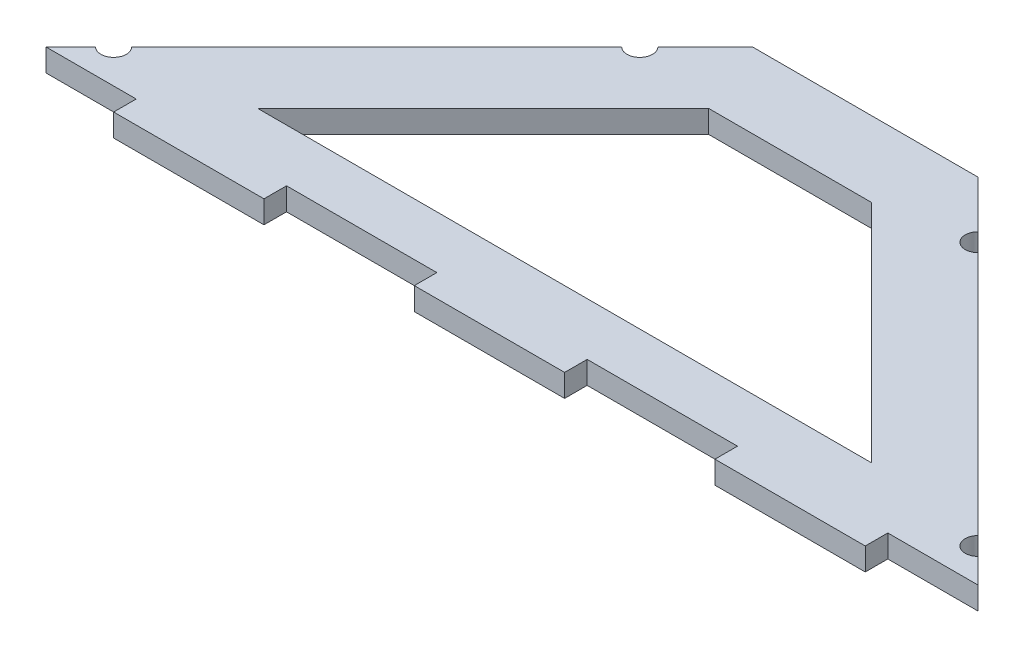
SolidWorks part; units mm, degrees
ref_plane "Front Plane" through (0, 0, 0) normal (0, 0, 1) x (1, 0, 0)
ref_plane "Top Plane" through (0, 0, 0) normal (0, 1, 0) x (1, 0, 0)
ref_plane "Right Plane" through (0, 0, 0) normal (1, 0, 0) x (0, 0, -1)
sketch "Sketch1" plane through (0, 0, 0) normal (0, 1, 0) x (1, 0, 0)
  line L0 (-55, 55) -> (-55, -55)
  line L1 (-65, 65) -> (65, 65)
  line L2 (-65, 65) -> (-65, -65)
  line L3 (-65, -65) -> (65, -65)
  line L4 (65, 65) -> (65, -65)
  line L5 (-65, 65) -> (65, -65) construction
  line L6 (-65, -65) -> (65, 65) construction
  line L7 (-55, -55) -> (55, -55)
  line L8 (55, 55) -> (55, -55)
  line L9 (-55, 55) -> (55, 55)
  line L10 (-15, 15) -> (-15, -15)
  line L11 (-15, -15) -> (15, -15)
  line L12 (15, 15) -> (15, -15)
  line L13 (-15, 15) -> (15, 15)
  line L14 (-25, 25) -> (-25, -25)
  line L15 (-25, -25) -> (25, -25)
  line L16 (25, 25) -> (25, -25)
  line L17 (-25, 25) -> (25, 25)
  line L18 (-55, -55) -> (-25, -25)
  line L19 (-47.9289, -62.0711) -> (-10.8579, -25)
  line L20 (-62.0711, -47.9289) -> (-25, -10.8579)
  line L21 (-62.0711, -47.9289) -> (-32.0711, -17.9289) construction
  line L22 (-47.9289, -62.0711) -> (-17.9289, -32.0711) construction
  line L23 (-47.9289, 62.0711) -> (-10.8579, 25)
  line L24 (-62.0711, 47.9289) -> (-25, 10.8579)
  line L25 (62.0711, 47.9289) -> (25, 10.8579)
  line L26 (47.9289, 62.0711) -> (10.8579, 25)
  line L27 (47.9289, -62.0711) -> (10.8579, -25)
  line L28 (62.0711, -47.9289) -> (25, -10.8579)
  point P0 (0, 0)
  point P39 (0, 0)
  dimension "D1" = 130
  dimension "D2" = 10
  dimension "D3" = 40
  dimension "D4" = 10
  dimension "D5" = 10
  dimension "D6" = 10
  dimension "D7" = 4
extrude "Boss-Extrude1" add sketch "Sketch1" along normal blind 3
sketch "Sketch2" plane through (0, 3, 0) normal (0, 1, 0) x (1, 0, 0)
  line L1 (-57.5, -57.5) -> (57.5, -57.5)
  line L2 (-57.5, -57.5) -> (-57.5, 57.5)
  line L3 (-57.5, 57.5) -> (57.5, 57.5)
  line L4 (57.5, -57.5) -> (57.5, 57.5)
  line L5 (-57.5, -57.5) -> (57.5, 57.5) construction
  line L6 (-57.5, 57.5) -> (57.5, -57.5) construction
  circle A0 centre (-57.5, 57.5) radius 1.7
  circle A1 centre (57.5, 57.5) radius 1.7
  circle A2 centre (57.5, -57.5) radius 1.7
  circle A3 centre (-57.5, -57.5) radius 1.7
  point P0 (0, 0)
  dimension "D2" = 3.4
  dimension "D1" = 115
extrude "Cut-Extrude1" cut sketch "Sketch2" against normal blind 3 contours L3 A0 L2 | L2 A0 L3 | L2 A3 L1 | L1 A3 L2 | L1 A2 L4 | L4 A2 L1 | L4 A1 L3 | L3 A1 L4
sketch "Sketch3" plane through (0, 3, 0) normal (0, 1, 0) x (1, 0, 0)
  line L1 (-22.5, -22.5) -> (22.5, -22.5)
  line L2 (-22.5, -22.5) -> (-22.5, 22.5)
  line L3 (-22.5, 22.5) -> (22.5, 22.5)
  line L4 (22.5, -22.5) -> (22.5, 22.5)
  line L5 (-22.5, -22.5) -> (22.5, 22.5) construction
  line L6 (-22.5, 22.5) -> (22.5, -22.5) construction
  circle A0 centre (-22.5, 22.5) radius 1.7
  circle A1 centre (22.5, 22.5) radius 1.7
  circle A2 centre (22.5, -22.5) radius 1.7
  circle A3 centre (-22.5, -22.5) radius 1.7
  point P0 (0, 0)
  dimension "D2" = 3.4
  dimension "D1" = 45
extrude "Cut-Extrude2" cut sketch "Sketch3" against normal blind 3 contours L2 A3 L1 | L1 A3 L2 | L2 A0 L3 | L3 A0 L2 | L1 A2 L4 | L4 A2 L1 | L4 A1 L3 | L3 A1 L4
sketch "Sketch4" plane through (0, 3, 0) normal (0, 1, 0) x (1, 0, 0)
  line L0 (-65, -65) -> (65, 65)
  line L1 (-65, 65) -> (65, -65)
  line L2 (65, -65) -> (-65, -65)
  line L3 (-15, -15) -> (15, -15)
  line L5 (-65, -65) -> (65, -65)
  line L6 (-65, -65) -> (-65, 65)
  line L7 (-65, 65) -> (65, 65)
  line L8 (65, -65) -> (65, 65)
  line L9 (-65, -65) -> (65, 65) construction
  line L10 (-65, 65) -> (65, -65) construction
  point P12 (0, 0)
  circle M1 centre (-22.5, 22.5) radius 1.7
  circle M2 centre (22.5, -22.5) radius 1.7
  circle M3 centre (22.5, 22.5) radius 1.7
  circle M4 centre (-22.5, -22.5) radius 1.7
  circle M5 centre (57.5, 57.5) radius 1.7
  circle M6 centre (57.5, -57.5) radius 1.7
  circle M7 centre (-57.5, -57.5) radius 1.7
  circle M8 centre (-57.5, 57.5) radius 1.7
  line M13 (-55, 40.8579) -> (-25, 10.8579)
  line M14 (-25, 10.8579) -> (-25, -10.8579)
  line M15 (-25, -10.8579) -> (-55, -40.8579)
  line M16 (-55, -40.8579) -> (-55, 40.8579)
  line M17 (10.8579, 25) -> (-10.8579, 25)
  line M18 (-10.8579, 25) -> (-40.8579, 55)
  line M19 (-40.8579, 55) -> (40.8579, 55)
  line M20 (40.8579, 55) -> (10.8579, 25)
  line M21 (25, -10.8579) -> (25, 10.8579)
  line M22 (25, 10.8579) -> (55, 40.8579)
  line M23 (55, 40.8579) -> (55, -40.8579)
  line M24 (55, -40.8579) -> (25, -10.8579)
  line M25 (65, -65) -> (65, 65)
  line M26 (65, 65) -> (-65, 65)
  line M27 (-65, 65) -> (-65, -65)
  line M29 (-15, -15) -> (-15, 15)
  line M30 (-15, 15) -> (15, 15)
  line M31 (15, 15) -> (15, -15)
extrude "Cut-Extrude3" cut sketch "Sketch4" against normal blind 10 contours M13 M16 M15 M14 | L1 L0 M27 M7 M4 M29 M1 M8 M16 M13 M14 M15 | L1 L0 M26 M8 M1 M30 M3 M5 M20 M17 M18 M19 | M17 M20 M19 M18 | L1 L0 M31 M2 M6 M25 M5 M3 M24 M21 M22 M23 | M21 M24 M23 M22 | L0 M7 | L0 M4 | L1 M2 | L1 M6
sketch "Sketch6" plane through (0, 3, 0) normal (0, 1, 0) x (1, 0, 0)
  line L0 (-65, -62) -> (-65, -65) construction
  line L1 (-50, -62) -> (-50, -65) construction
  line L2 (-30, -62) -> (-30, -65) construction
  line L3 (-10, -62) -> (-10, -65) construction
  line L4 (10, -62) -> (10, -65) construction
  line L5 (30, -62) -> (30, -65) construction
  line L6 (50, -62) -> (50, -65) construction
  line L7 (50, -62) -> (65, -62) construction
  line L8 (50, -65) -> (65, -65) construction
  line L9 (-65, -62) -> (-65, -65)
  line L10 (-50, -62) -> (-50, -65)
  line L11 (-30, -62) -> (-30, -65)
  line L12 (-10, -62) -> (-10, -65)
  line L13 (10, -62) -> (10, -65)
  line L14 (30, -62) -> (30, -65)
  line L15 (50, -62) -> (50, -65)
  line L16 (50, -62) -> (65, -62)
  line L17 (50, -65) -> (65, -65)
  line L18 (65, -62) -> (65, -65)
  line L19 (65, -62) -> (-65, -62)
  line L20 (65, -65) -> (-65, -65)
  line L21 (-65, -62) -> (-65, -65)
  line M1 (-58.7021, -58.7021) -> (-65, -65)
  line M2 (-65, -65) -> (65, -65)
  line M3 (65, -65) -> (58.7021, -58.7021)
extrude "Cut-Extrude4" cut sketch "Sketch6" against normal blind 10 contours L10 L19 M1 M2 | L12 L19 L11 M2 | L14 L19 L13 M2 | L16 L15 M2 M3
